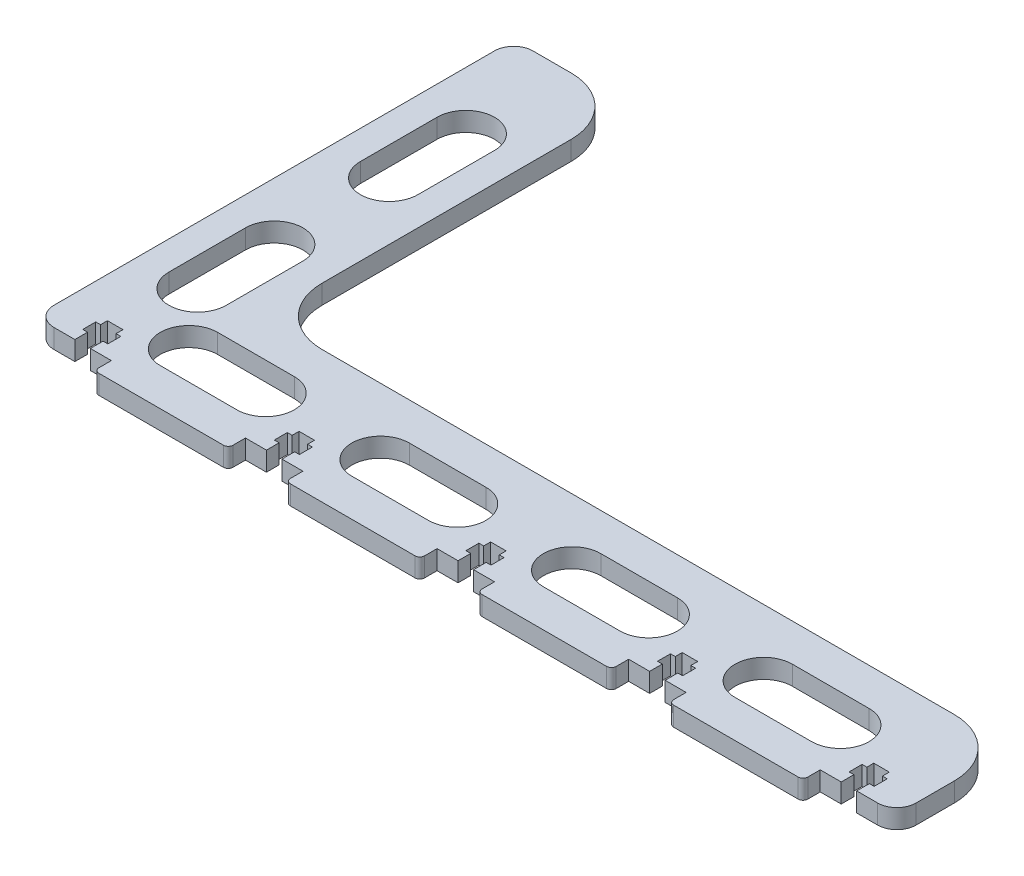
SolidWorks part; units mm, degrees
ref_plane "Front Plane" through (0, 0, 0) normal (0, 0, 1) x (1, 0, 0)
ref_plane "Top Plane" through (0, 0, 0) normal (0, 1, 0) x (1, 0, 0)
ref_plane "Right Plane" through (0, 0, 0) normal (1, 0, 0) x (0, 0, -1)
sketch "Sketch1" plane through (0, 0, 0) normal (0, 1, 0) x (1, 0, 0)
  line L1 (0, 0) -> (450, 0)
  line L2 (450, 450) -> (0, 450)
  line L3 (0, 450) -> (0, 0)
  line L4 (450, 0) -> (450, 450)
  dimension "D1" = 450
  dimension "D2" = 450
extrude "Boss-Extrude1" add sketch "Sketch1" along normal blind 10
sketch "Sketch2" plane through (0, 10, 0) normal (0, 1, 0) x (1, 0, 0)
  line L0 (225, 13.4) -> (225, 0) construction
  line L2 (0, 0) -> (450, 0) construction
  line L3 (0, 0) -> (450, 0) construction
  line L4 (220.95, 17) -> (229.05, 17)
  line L5 (220.95, 17) -> (220.95, -10)
  line L6 (220.95, -10) -> (229.05, -10)
  line L7 (229.05, 17) -> (229.05, -10)
  line L8 (220.95, 17) -> (229.05, -10) construction
  line L9 (220.95, -10) -> (229.05, 17) construction
  line L10 (218.45, 13.4) -> (231.55, 13.4)
  line L11 (218.45, 13.4) -> (218.45, 6.6)
  line L12 (218.45, 6.6) -> (231.55, 6.6)
  line L13 (231.55, 13.4) -> (231.55, 6.6)
  line L14 (218.45, 13.4) -> (231.55, 6.6) construction
  line L15 (218.45, 6.6) -> (231.55, 13.4) construction
  point P6 (225, 3.5)
  point P11 (225, 10)
  dimension "D1" = 10
  dimension "D2" = 27
  dimension "D3" = 8.1
  dimension "D4" = 13.1
  dimension "D5" = 6.8
  dimension "D6" = 10
extrude "Cut-Extrude1" cut sketch "Sketch2" against normal through all contours L7 L6 L5 L4 | L10 L13 L12 L11
pattern_linear "LPattern1" count 3 spacing 100 along (-1, 0, 0) count 3 spacing 100 along (1, 0, 0) of "Cut-Extrude1"
sketch "Sketch3" plane through (0, 10, 0) normal (0, 1, 0) x (1, 0, 0)
  line L0 (75, 0) -> (75, -40.4892) construction
  line L1 (29.05, 0) -> (120.95, 0) construction
  line L3 (40, -9) -> (110, -9)
  line L4 (40, -9) -> (40, 0)
  line L5 (40, 0) -> (110, 0)
  line L6 (110, -9) -> (110, 0)
  line L7 (40, -9) -> (110, 0) construction
  line L8 (40, 0) -> (110, -9) construction
  point P4 (75, -4.5)
  dimension "D1" = 9
  dimension "D2" = 70
extrude "Boss-Extrude2" add sketch "Sketch3" against normal blind 10
fillet "Fillet1" radius 2.5 2 edges at (110, 5, 9) (40, 5, 9)
pattern_linear "LPattern2" count 4 spacing 100 along (1, 0, 0) of "Fillet1", "Boss-Extrude2"
sketch "Sketch4" plane through (0, 10, 0) normal (0, 1, 0) x (1, 0, 0)
  line L0 (0, 450) -> (0, 0) construction
  line L1 (450, 450) -> (60, 450)
  line L2 (450, 450) -> (450, 60)
  line L3 (450, 60) -> (60, 60)
  line L4 (60, 450) -> (60, 60)
  line L5 (429.05, 0) -> (450, 0) construction
  line L6 (0, 0) -> (20.95, 0) construction
  line L8 (60, 450) -> (0, 450)
  line L9 (60, 450) -> (60, 250)
  line L10 (60, 250) -> (0, 250)
  line L11 (0, 450) -> (0, 250)
  dimension "D1" = 60
  dimension "D2" = 60
  dimension "D3" = 250
extrude "Cut-Extrude2" cut sketch "Sketch4" against normal through all contours L1 L4 L3 L2 | L8 L11 L10 L4
sketch "Sketch5" plane through (0, 10, 0) normal (0, 1, 0) x (1, 0, 0)
  line L0 (375, -9) -> (375, 60) construction
  line L1 (342.5, -9) -> (407.5, -9) construction
  line L2 (450, 60) -> (60, 60) construction
  line L3 (275, -9) -> (275, 60) construction
  line L4 (242.5, -9) -> (307.5, -9) construction
  line L5 (175, -9) -> (175, 60) construction
  line L6 (142.5, -9) -> (207.5, -9) construction
  line L7 (75, -9) -> (75, 60) construction
  line L8 (42.5, -9) -> (107.5, -9) construction
  line L9 (55, 25.5) -> (95, 25.5) construction
  line L10 (55, 40.5) -> (95, 40.5)
  line L11 (55, 10.5) -> (95, 10.5)
  line L12 (155, 25.5) -> (195, 25.5) construction
  line L13 (155, 40.5) -> (195, 40.5)
  line L14 (155, 10.5) -> (195, 10.5)
  line L15 (255, 25.5) -> (295, 25.5) construction
  line L16 (255, 40.5) -> (295, 40.5)
  line L17 (255, 10.5) -> (295, 10.5)
  line L18 (355, 25.5) -> (395, 25.5) construction
  line L19 (355, 40.5) -> (395, 40.5)
  line L20 (355, 10.5) -> (395, 10.5)
  line L21 (0, 75) -> (60, 75) construction
  line L22 (0, 250) -> (0, 0) construction
  line L23 (60, 250) -> (60, 60) construction
  line L24 (0, 175) -> (60, 175) construction
  line L25 (0, 0) -> (20.95, 0) construction
  line L27 (30, 55) -> (30, 95) construction
  line L28 (15, 55) -> (15, 95)
  line L29 (45, 55) -> (45, 95)
  line L30 (30, 195) -> (30, 155) construction
  line L31 (45, 195) -> (45, 155)
  line L32 (15, 195) -> (15, 155)
  arc A0 (55, 40.5) -> (55, 10.5) centre (55, 25.5) ccw
  arc A1 (95, 10.5) -> (95, 40.5) centre (95, 25.5) ccw
  arc A2 (155, 40.5) -> (155, 10.5) centre (155, 25.5) ccw
  arc A3 (195, 10.5) -> (195, 40.5) centre (195, 25.5) ccw
  arc A4 (255, 40.5) -> (255, 10.5) centre (255, 25.5) ccw
  arc A5 (295, 10.5) -> (295, 40.5) centre (295, 25.5) ccw
  arc A6 (355, 40.5) -> (355, 10.5) centre (355, 25.5) ccw
  arc A7 (395, 10.5) -> (395, 40.5) centre (395, 25.5) ccw
  arc A8 (15, 55) -> (45, 55) centre (30, 55) ccw
  arc A9 (45, 95) -> (15, 95) centre (30, 95) ccw
  arc A10 (45, 195) -> (15, 195) centre (30, 195) ccw
  arc A11 (15, 155) -> (45, 155) centre (30, 155) ccw
  point P20 (75, 25.5)
  point P27 (175, 25.5)
  point P34 (275, 25.5)
  point P41 (375, 25.5)
  point P60 (30, 75)
  point P67 (30, 175)
  dimension "D1" = 40
  dimension "D2" = 30
  dimension "D3" = 40
  dimension "D4" = 30
  dimension "D5" = 40
  dimension "D6" = 30
  dimension "D7" = 40
  dimension "D8" = 30
  dimension "D9" = 75
  dimension "D10" = 100
  dimension "D12" = 40
  dimension "D13" = 30
  dimension "D14" = 40
  dimension "D15" = 30
extrude "Cut-Extrude3" cut sketch "Sketch5" against normal through all
fillet "Fillet2" radius 10 3 edges at (450, 5, 0) (0, 5, 0) (0, 5, -250)
fillet "Fillet3" radius 30 3 edges at (450, 5, -60) (60, 5, -60) (60, 5, -250)
